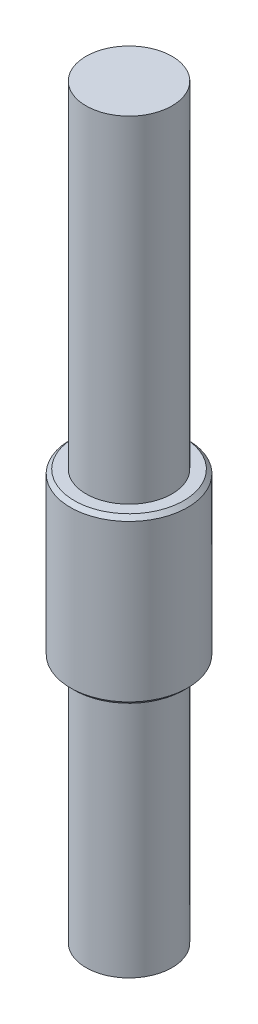
SolidWorks part; units mm, degrees
ref_plane "Front Plane" through (0, 0, 0) normal (0, 0, 1) x (1, 0, 0)
ref_plane "Top Plane" through (0, 0, 0) normal (0, 1, 0) x (1, 0, 0)
ref_plane "Right Plane" through (0, 0, 0) normal (1, 0, 0) x (0, 0, -1)
sketch "Sketch1" plane through (0, 0, 0) normal (0, 0, 1) x (1, 0, 0)
  line L0 (0, 0) -> (0, 8.6394) construction
  line L1 (0, 0) -> (5.5, 0)
  line L2 (5.5, 0) -> (5.5, 31.5)
  line L3 (5.5, 31.5) -> (7, 31.5)
  line L4 (7.5, 32) -> (7.5, 52)
  line L5 (7, 52.5) -> (5.5, 52.5)
  line L6 (7.5, 52) -> (7, 52.5)
  line L7 (7, 31.5) -> (7.5, 32)
  line L8 (5.5, 52.5) -> (5.5, 95.5)
  line L9 (5.5, 95.5) -> (0, 95.5)
  line L10 (0, 95.5) -> (0, 0)
  point P8 (7.5, 31.5)
  point P9 (7.5, 52.5)
  dimension "D1" = 5.5
  dimension "D2" = 31.5
  dimension "D3" = 2
  dimension "D4" = 21
  dimension "D5" = 43
revolve "Revolve1" add sketch "Sketch1" angle 360 about L0
hole_wizard "M6x1.0 Tapped Hole1" positions "Sketch3" profile "Sketch2" tap size "M6x1.0" standard "ANSI Metric"
sketch "Sketch3" plane through (0, 0, 0) normal (0, -1, 0) x (-1, 0, 0)
  point P0 (0, 0)
sketch "Sketch2" plane through (0, 0, 0) normal (1, 0, 0) x (0, 0, -1)
  line L0 (0, 0) -> (0, 8.5022)
  line L1 (0, 8.5022) -> (2.5, 7)
  line L2 (2.5, 7) -> (2.5, 0)
  line L5 (2.5, 0) -> (0, 0)
  line L10 (0, 8.5022) -> (-2.5, 7) construction
  line L11 (0, -6.35) -> (0, 107.95) construction
  dimension "Tap Drill Dia." = 5
  dimension "Tap Drill Depth" = 7
  dimension "Drill Angle" = 118
cosmetic thread "Hole Thread1" parameters "D1"=7, "D2"=6
